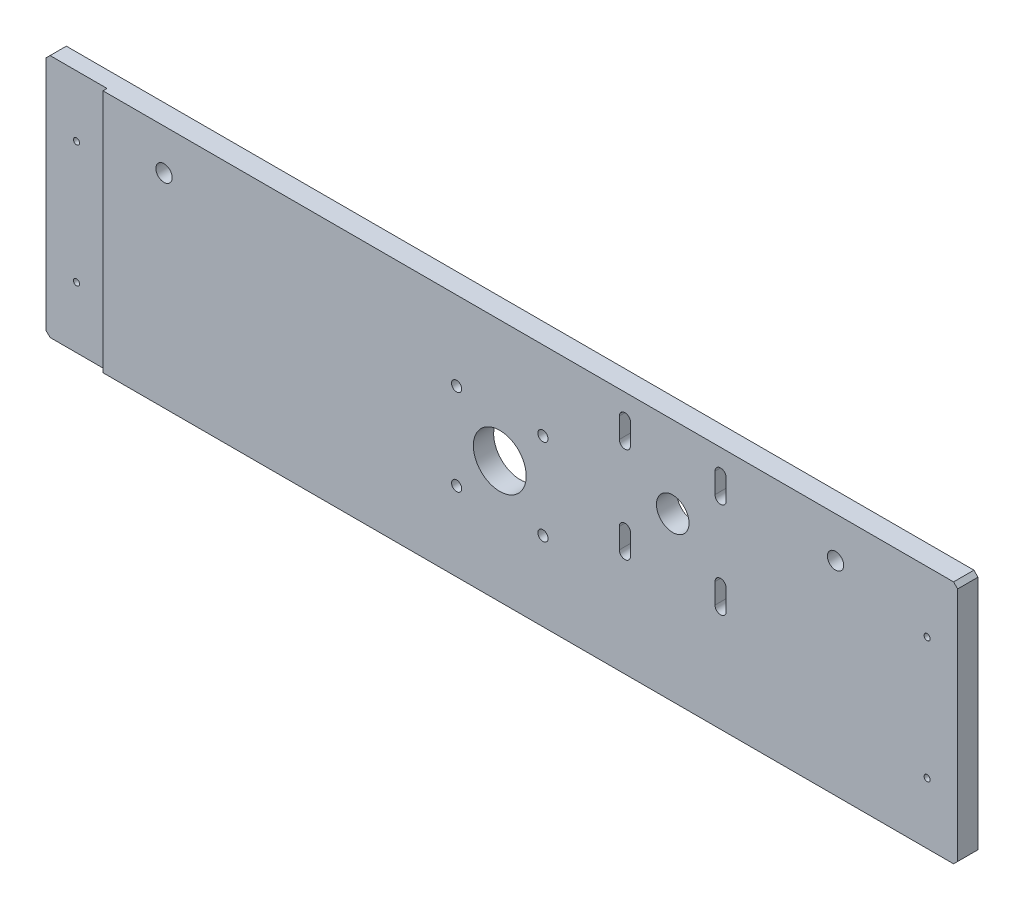
SolidWorks part; units mm, degrees
ref_plane "Piano frontale" through (0, 0, 0) normal (0, 0, 1) x (1, 0, 0)
ref_plane "Piano superiore" through (0, 0, 0) normal (0, 1, 0) x (1, 0, 0)
ref_plane "Piano destro" through (0, 0, 0) normal (1, 0, 0) x (0, 0, -1)
sketch "Schizzo1" plane through (0, 0, 0) normal (0, 0, 1) x (1, 0, 0)
  line L0 (225, 120) -> (225, 0) construction
  line L1 (2, 0) -> (448, 0)
  line L2 (0, 2) -> (0, 118)
  line L3 (2, 120) -> (448, 120)
  line L4 (450, 2) -> (450, 118)
  line L7 (225, 60) -> (243.5099, 60) construction
  line L8 (459.2931, 100) -> (370.8276, 100) construction
  line L9 (225, 60) -> (194.6932, 90.3068) construction
  line L21 (0, 118) -> (2, 120)
  line L22 (2, 0) -> (0, 2)
  line L23 (448, 0) -> (450, 2)
  line L24 (448, 120) -> (450, 118)
  line L25 (225, 60) -> (450, 60) construction
  line L26 (344.754, 80) -> (282.8483, 80) construction
  line L27 (333.5, 108.5) -> (333.5, 98.5) construction
  line L28 (330.75, 108.5) -> (330.75, 98.5)
  line L29 (336.25, 108.5) -> (336.25, 98.5)
  line L30 (286.5, 108.5) -> (286.5, 98.5) construction
  line L31 (289.25, 108.5) -> (289.25, 98.5)
  line L32 (283.75, 108.5) -> (283.75, 98.5)
  line L33 (333.5, 51.5) -> (333.5, 61.5) construction
  line L34 (330.75, 51.5) -> (330.75, 61.5)
  line L35 (336.25, 51.5) -> (336.25, 61.5)
  line L36 (286.5, 51.5) -> (286.5, 61.5) construction
  line L37 (289.25, 51.5) -> (289.25, 61.5)
  line L38 (283.75, 51.5) -> (283.75, 61.5)
  line L42 (310, 120) -> (310, 0) construction
  circle A0 centre (225, 60) radius 13
  circle A1 centre (225, 60) radius 30 construction
  circle A2 centre (246.2132, 81.2132) radius 2.5
  circle A3 centre (390, 100) radius 4
  circle A4 centre (246.2132, 38.7868) radius 2.5
  circle A5 centre (203.7868, 38.7868) radius 2.5
  circle A10 centre (60, 100) radius 4
  circle A11 centre (15, 30) radius 1.5
  circle A12 centre (435, 30) radius 1.5
  circle A13 centre (203.7868, 81.2132) radius 2.5
  circle A17 centre (435, 90) radius 1.5
  circle A18 centre (15, 90) radius 1.5
  arc A19 (330.75, 108.5) -> (336.25, 108.5) centre (333.5, 108.5) cw
  arc A20 (336.25, 98.5) -> (330.75, 98.5) centre (333.5, 98.5) cw
  arc A21 (289.25, 108.5) -> (283.75, 108.5) centre (286.5, 108.5) ccw
  arc A22 (283.75, 98.5) -> (289.25, 98.5) centre (286.5, 98.5) ccw
  arc A23 (330.75, 51.5) -> (336.25, 51.5) centre (333.5, 51.5) ccw
  arc A24 (336.25, 61.5) -> (330.75, 61.5) centre (333.5, 61.5) ccw
  arc A25 (289.25, 51.5) -> (283.75, 51.5) centre (286.5, 51.5) cw
  arc A26 (283.75, 61.5) -> (289.25, 61.5) centre (286.5, 61.5) cw
  circle A27 centre (310, 80) radius 8
  point P0 (0, 0)
  point P1 (450, 120)
  point P2 (0, 120)
  point P3 (450, 0)
  point P9 (203.7868, 81.2132)
  point P13 (203.7868, 81.2132)
  point P80 (310, 80)
  point P83 (333.5, 103.5)
  point P90 (286.5, 103.5)
  point P97 (333.5, 56.5)
  point P104 (286.5, 56.5)
  dimension "D4" = 26
  dimension "D10" = 8
  dimension "D15" = 3
  dimension "D17" = 5
  dimension "D25" = 16
  dimension "D8" = 45
  dimension "D1" = 120
  dimension "D2" = 450
  dimension "D3" = 60
  dimension "D7" = 20
  dimension "D12" = 60
  dimension "D14" = 30
  dimension "D16" = 15
  dimension "D18" = 40
  dimension "D23" = 23.5
  dimension "D24" = 23.5
  dimension "D26" = 5.5
  dimension "D27" = 10
  dimension "D29" = 140
extrude "Estrusione-Estrusione1" add sketch "Schizzo1" against normal blind 10
sketch "Schizzo2" plane through (0, 0, 0) normal (0, 0, 1) x (1, 0, 0)
  line L0 (448, 120) -> (2, 120) construction
  line L1 (30, 120) -> (0, 120)
  line L2 (30, 120) -> (30, 0)
  line L3 (30, 0) -> (0, 0)
  line L4 (0, 120) -> (0, 0)
  line L5 (315.2194, 120) -> (315.2194, -23.5993) construction
  line L6 (630.4389, 120) -> (630.4389, 0)
  line L7 (600.4389, 0) -> (630.4389, 0)
  line L8 (600.4389, 120) -> (600.4389, 0)
  line L9 (600.4389, 120) -> (630.4389, 120)
  dimension "D1" = 30
extrude "Taglio-Estrusione1" cut sketch "Schizzo2" against normal blind 2
